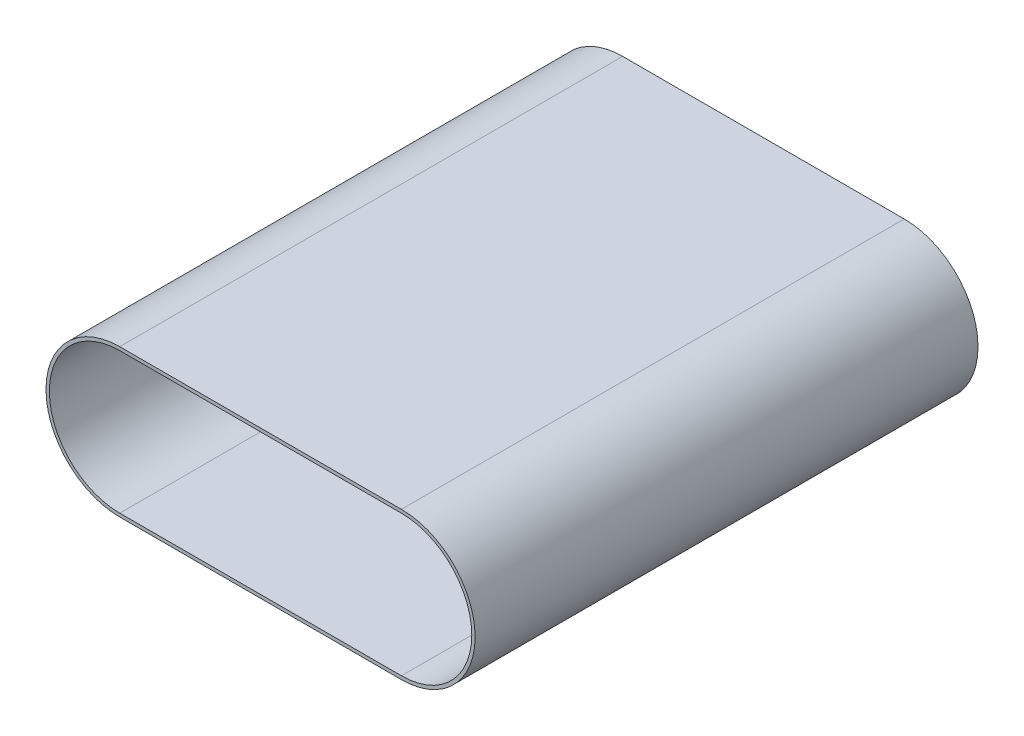
SolidWorks part; units mm, degrees
ref_plane "Front Plane" through (0, 0, 0) normal (0, 0, 1) x (1, 0, 0)
ref_plane "Top Plane" through (0, 0, 0) normal (0, 1, 0) x (1, 0, 0)
ref_plane "Right Plane" through (0, 0, 0) normal (1, 0, 0) x (0, 0, -1)
sketch "Sketch2" plane through (0, 0, 0) normal (0, 0, 1) x (1, 0, 0)
  line L0 (-533.4, 0) -> (533.4, 0) construction
  line L1 (-533.4, 279.4) -> (533.4, 279.4)
  line L2 (-533.4, -279.4) -> (533.4, -279.4)
  line L3 (-533.4, 266.7) -> (533.4, 266.7)
  line L4 (-533.4, -266.7) -> (533.4, -266.7)
  arc A0 (-533.4, 279.4) -> (-533.4, -279.4) centre (-533.4, 0) ccw
  arc A1 (533.4, -279.4) -> (533.4, 279.4) centre (533.4, 0) ccw
  arc A2 (533.4, -266.7) -> (533.4, 266.7) centre (533.4, 0) ccw
  arc A3 (-533.4, 266.7) -> (-533.4, -266.7) centre (-533.4, 0) ccw
  point P2 (0, 0)
  dimension "D4" = 266.7
  dimension "D2" = 1066.8
  dimension "D3" = 12.7
extrude "Boss-Extrude1" add sketch "Sketch2" against normal blind 1905 contours L2 A1 L1 A0 | L3 A2 L4 A3
